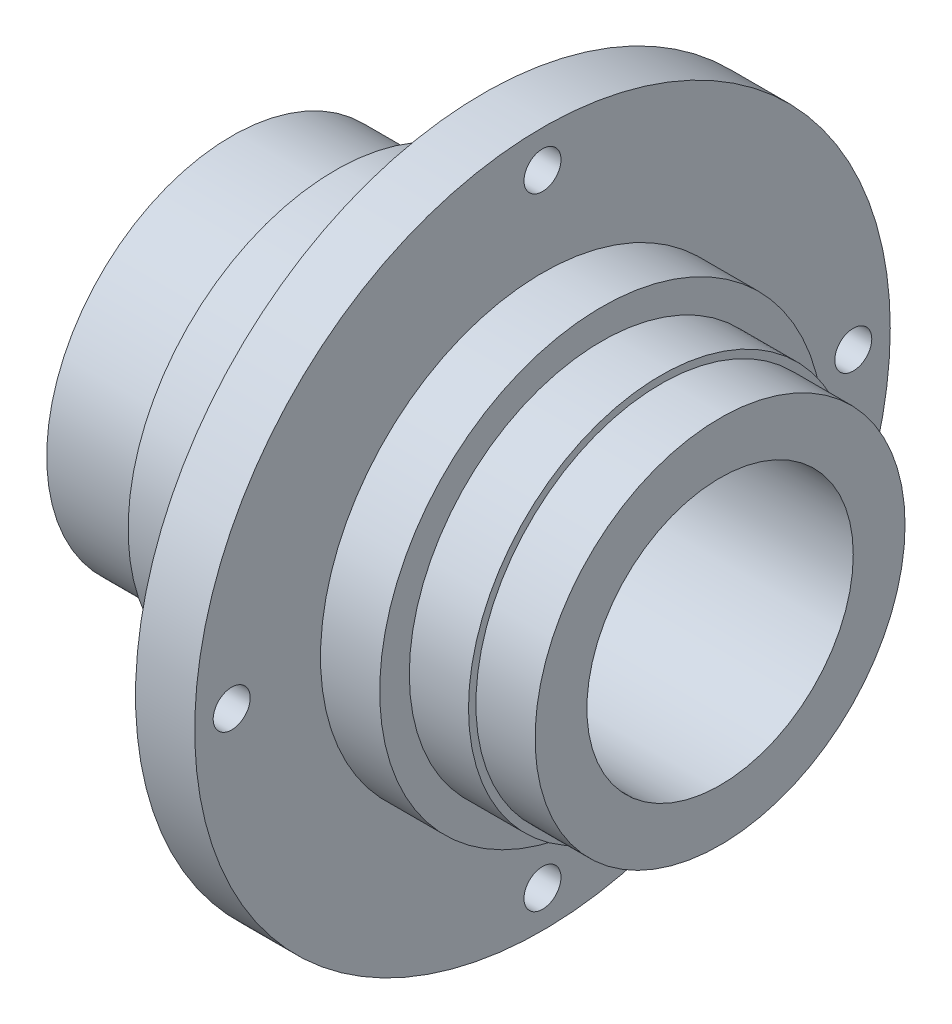
SolidWorks part; units mm, degrees
material "6061-T6 (SS)"
ref_plane "前视基准面" through (0, 0, 0) normal (0, 0, 1) x (1, 0, 0)
ref_plane "上视基准面" through (0, 0, 0) normal (0, 1, 0) x (1, 0, 0)
ref_plane "右视基准面" through (0, 0, 0) normal (1, 0, 0) x (0, 0, -1)
sketch "草图1" plane through (0, 0, 0) normal (1, 0, 0) x (0, 0, -1)
  circle A0 centre (0, 0) radius 12.5
  dimension "D1" = 25
extrude "凸台-拉伸1" add sketch "草图1" along normal blind 7
sketch "草图2" plane through (7, 0, 0) normal (1, 0, 0) x (0, 0, -1)
  circle A0 centre (0, 0) radius 14
  dimension "D1" = 28
extrude "凸台-拉伸2" add sketch "草图2" along normal blind 10
sketch "草图3" plane through (17, 0, 0) normal (1, 0, 0) x (0, 0, -1)
  circle A0 centre (0, 0) radius 23.5
  dimension "D1" = 47
extrude "凸台-拉伸3" add sketch "草图3" along normal blind 4
sketch "草图5" plane through (0, 0, 0) normal (-1, 0, 0) x (0, 0, 1)
  line L0 (0, 0) -> (0, 11) construction
  circle A0 centre (0, 11) radius 1
  circle A1 centre (11, 0) radius 1
  circle A2 centre (0, -11) radius 1
  circle A3 centre (-11, 0) radius 1
  dimension "D3" = 2
  dimension "D2" = 11
  dimension "D1" = 4
sketch "草图6" plane through (21, 0, 0) normal (1, 0, 0) x (0, 0, -1)
  line L0 (0, 0) -> (0, 21) construction
  circle A0 centre (0, 21) radius 1.6
  circle A1 centre (21, 0) radius 1.6
  circle A2 centre (0, -21) radius 1.6
  circle A3 centre (-21, 0) radius 1.6
  dimension "D3" = 3.2
  dimension "D2" = 21
  dimension "D1" = 4
hole_wizard "M3 螺纹孔1" positions "草图8" profile "草图9" tap size "M3" standard "GB"
sketch "草图8" plane through (21, 0, 0) normal (1, 0, 0) x (0, 0, -1)
  point P0 (0, 21)
  point P3 (21, 0)
  point P6 (0, -21)
  point P9 (-21, 0)
sketch "草图9" plane through (21, 21, 0) normal (0, 1, 0) x (0, 0, -1)
  line L0 (0, 0) -> (0, 9.2511)
  line L1 (0, 9.2511) -> (1.25, 8.5)
  line L2 (1.25, 8.5) -> (1.25, 0)
  line L5 (1.25, 0) -> (0, 0)
  line L10 (0, 9.2511) -> (-1.25, 8.5) construction
  line L11 (0, -6.35) -> (0, 107.95) construction
  dimension "螺纹孔钻头直径" = 2.5
  dimension "螺纹孔钻头深度" = 8.5
  dimension "导头角度" = 118
cosmetic thread "孔螺蚊线5" parameters "D1"=6, "D2"=3
cosmetic thread "孔螺蚊线6" parameters "D1"=6, "D2"=3
cosmetic thread "孔螺蚊线7" parameters "D1"=6, "D2"=3
cosmetic thread "孔螺蚊线8" parameters "D1"=6, "D2"=3
hole_wizard "M2 螺纹孔1" positions "草图10" profile "草图11" tap size "M2" standard "GB"
sketch "草图10" plane through (0, 0, 0) normal (-1, 0, 0) x (0, 0, 1)
  point P0 (-11, 0)
  point P3 (0, -11)
  point P6 (11, 0)
  point P9 (0, 11)
sketch "草图11" plane through (0, 0, -11) normal (0, 1, 0) x (0, 0, 1)
  line L0 (0, 0) -> (0, 6.4807)
  line L1 (0, 6.4807) -> (0.8, 6)
  line L2 (0.8, 6) -> (0.8, 0)
  line L5 (0.8, 0) -> (0, 0)
  line L10 (0, 6.4807) -> (-0.8, 6) construction
  line L11 (0, -6.35) -> (0, 107.95) construction
  dimension "螺纹孔钻头直径" = 1.6
  dimension "螺纹孔钻头深度" = 6
  dimension "导头角度" = 118
cosmetic thread "孔螺蚊线9" parameters "D1"=4, "D2"=2
cosmetic thread "孔螺蚊线10" parameters "D1"=4, "D2"=2
cosmetic thread "孔螺蚊线11" parameters "D1"=4, "D2"=2
cosmetic thread "孔螺蚊线12" parameters "D1"=4, "D2"=2
sketch "草图14" plane through (21, 0, 0) normal (1, 0, 0) x (0, 0, -1)
  circle A0 centre (0, 0) radius 15
  dimension "D1" = 30
extrude "凸台-拉伸4" add sketch "草图14" along normal blind 4
sketch "草图15" plane through (25, 0, 0) normal (1, 0, 0) x (0, 0, -1)
  circle A0 centre (0, 0) radius 13
  dimension "D1" = 26
extrude "凸台-拉伸5" add sketch "草图15" along normal blind 4
sketch "草图16" plane through (29, 0, 0) normal (1, 0, 0) x (0, 0, -1)
  circle A0 centre (0, 0) radius 12.5
  dimension "D1" = 25
extrude "凸台-拉伸6" add sketch "草图16" along normal blind 4
sketch "草图4" plane through (0, 0, 0) normal (1, 0, 0) x (0, 0, -1)
  circle A0 centre (0, 0) radius 9
  dimension "D1" = 18
extrude "切除-拉伸2" cut sketch "草图4" along normal through all
